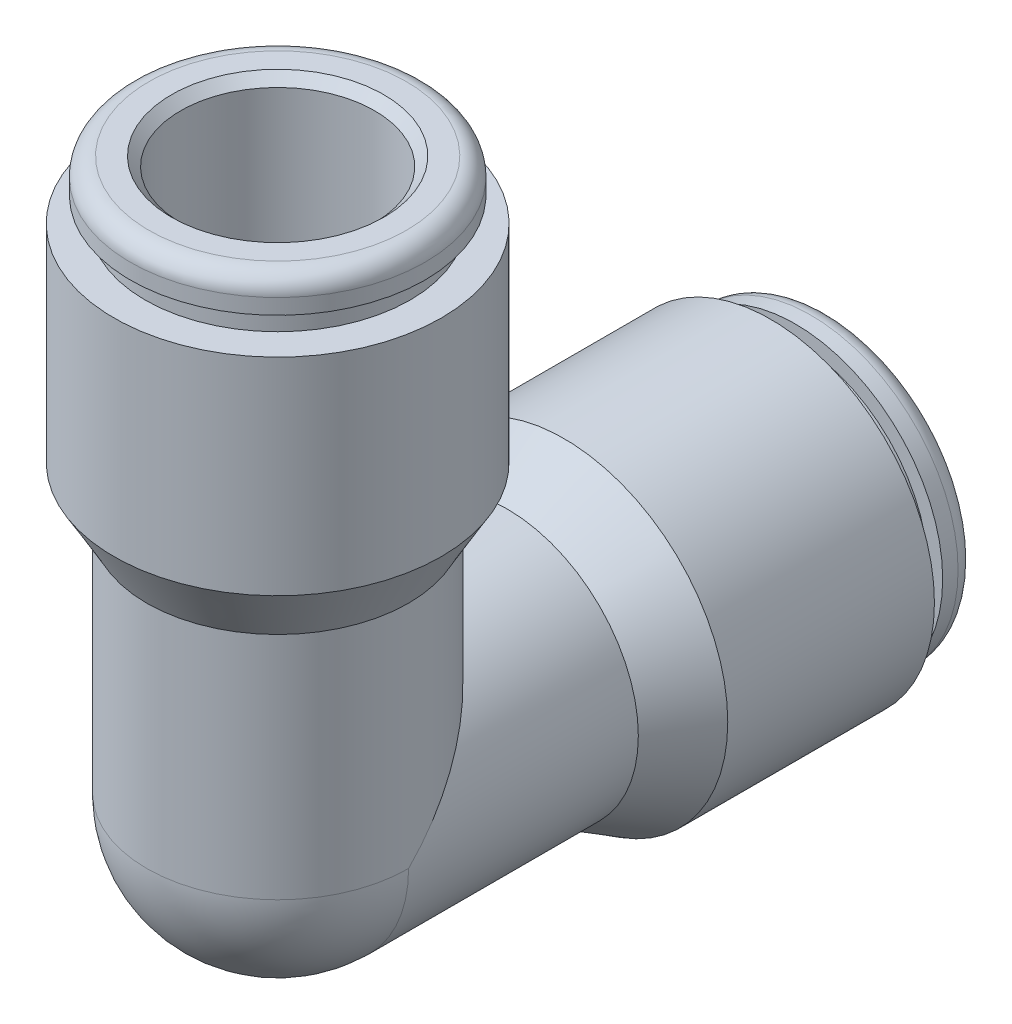
SolidWorks part; units mm, degrees
ref_plane "Front Plane" through (0, 0, 0) normal (0, 0, 1) x (1, 0, 0)
ref_plane "Top Plane" through (0, 0, 0) normal (0, 1, 0) x (1, 0, 0)
ref_plane "Right Plane" through (0, 0, 0) normal (1, 0, 0) x (0, 0, -1)
sketch "Sketch1" plane through (0, 0, 0) normal (1, 0, 0) x (0, 0, -1)
  line L0 (21.353, 6.075) -> (21.988, 6.075)
  line L1 (11.8133, 6.75) -> (20.337, 6.75)
  line L2 (0, 5.4) -> (0, 3.238)
  line L3 (8, 4) -> (22.369, 4)
  line L4 (22.75, 5.313) -> (22.75, 4.381)
  line L5 (0, 0) -> (0, 22.75) construction
  line L6 (20.337, 6.75) -> (20.337, 5.4675)
  line L7 (20.337, 5.4675) -> (21.353, 5.4675)
  line L8 (21.353, 6.075) -> (21.353, 5.4675)
  line L9 (-6.75, 22.75) -> (6.75, 22.75) construction
  line L10 (0, 0) -> (22.75, 0) construction
  line L11 (8, 4) -> (8, 3.238)
  line L12 (22.369, 4) -> (22.75, 4.381)
  line L13 (0, 0) -> (0, 3.238) construction
  line L14 (0, 5.4) -> (9.475, 5.4)
  line L15 (9.475, 5.4) -> (11.8133, 6.75)
  line L16 (8, 3.238) -> (0, 3.238)
  arc A0 (21.988, 6.075) -> (22.75, 5.313) centre (21.988, 5.313) cw
  point P1 (22.75, 4)
  point P20 (22.75, 6.075)
  dimension "D4" = 0.762
  dimension "tube od" = 8
  dimension "D1" = 1.397
  dimension "D2" = 1.016
  dimension "D3" = 10.935
  dimension "D6" = 12.15
  dimension "D9" = 30
  dimension "D10" = 10.8
  dimension "D5" = 13.275
  dimension "D8" = 13.5
  dimension "D11" = 0.762
revolve "Revolve1" add sketch "Sketch1" angle 360 about L10
ref_axis "Axis1" through (-7.425, 0, 0) along (1, 0, 0)
pattern_circular "CirPattern1" count 2 over 90 about axis through (-7.425, 0, 0) along (1, 0, 0) of bodies 118 123
sketch "Sketch2" plane through (0, 0, 0) normal (0, 0, 1) x (1, 0, 0)
  line L0 (-5.4, 0) -> (-3.238, 0)
  line L1 (-5.4, 0) -> (5.4, 0) construction
  line L2 (3.238, 0) -> (5.4, 0)
  arc A0 (-5.4, 0) -> (5.4, 0) centre (0, 0) ccw
  arc A2 (-3.238, 0) -> (3.238, 0) centre (0, 0) ccw
  circle A4 centre (0, 0) radius 3.238 construction
  circle A5 centre (0, 0) radius 5.4 construction
revolve "Revolve2" add sketch "Sketch2" angle 90 about L1
combine bodies "Combine1" operation type add bodies to combine 122 124
sketch "Sketch3" plane through (0, 0, 0) normal (1, 0, 0) x (0, 0, -1)
  line L0 (22.75, 4.381) -> (22.369, 4)
  line L1 (22.369, 4) -> (8, 4)
  line L2 (8, 4) -> (8, 3.238)
  line L3 (8, 3.238) -> (0, 3.238)
  line L4 (0, 3.238) -> (0, 0)
  line L5 (0, 0) -> (22.75, 0)
  line L6 (22.75, 0) -> (22.75, 4.381)
revolve "Cut-Revolve1" cut sketch "Sketch3" angle 360 about L5
pattern_circular "CirPattern2" count 2 over 90 about axis through (-7.425, 0, 0) along (1, 0, 0) of "Cut-Revolve1"
equation "\"D6@Sketch1\" = \"G@Sketch1\"*.9"
equation "\"D3@Sketch1\" = \"D6@Sketch1\"*.9"
equation "\"D10@Sketch1\" = \"G@Sketch1\"*.8"
equation "\"D5@Sketch1\" = \"L@Sketch1\"*.45"
equation "\"D8@Sketch1\" = \"G@Sketch1\""
